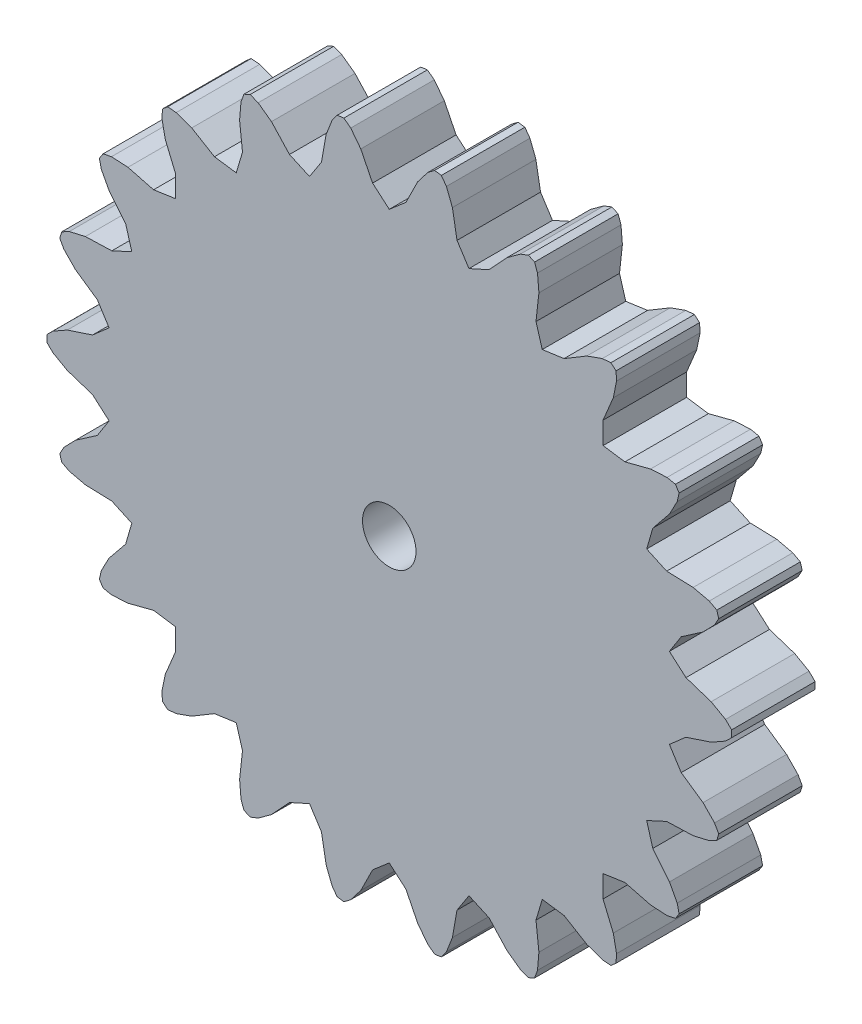
SolidWorks part; units mm, degrees
ref_plane "Front Plane" through (0, 0, 0) normal (0, 0, 1) x (1, 0, 0)
ref_plane "Top Plane" through (0, 0, 0) normal (0, 1, 0) x (1, 0, 0)
ref_plane "Right Plane" through (0, 0, 0) normal (1, 0, 0) x (0, 0, -1)
sketch "Sketch1" plane through (0, 0, 0) normal (0, 0, 1) x (1, 0, 0)
  line L1 (1.2374, -1.2374) -> (-1.2374, -1.2374) construction
  line L2 (1.2374, -1.2374) -> (1.2374, 1.2374) construction
  line L3 (1.2374, 1.2374) -> (-1.2374, 1.2374) construction
  line L4 (-1.2374, -1.2374) -> (-1.2374, 1.2374) construction
  line L5 (1.2374, -1.2374) -> (-1.2374, 1.2374) construction
  line L6 (1.2374, 1.2374) -> (-1.2374, -1.2374) construction
  circle A0 centre (0, 0) radius 20.5
  circle A1 centre (0, 0) radius 1.75 construction
  dimension "D1" = 41
  dimension "D2" = 3.5
extrude "Boss-Extrude1" add sketch "Sketch1" along normal blind 5
sketch "Sketch2" plane through (0, 0, 0) normal (0, 0, 1) x (1, 0, 0)
  line L0 (0, 0) -> (0, 10.088) construction
  line L1 (0, 16.9447) -> (-0.9985, 17.8041)
  line L8 (-2.7154, 20.3194) -> (0, 24.5037)
  line L11 (-0.9985, 17.8041) -> (-1.7043, 19.2252)
  line L12 (-1.7043, 19.2252) -> (-2.3066, 20.0063)
  line L13 (-2.3066, 20.0063) -> (-2.7154, 20.3194)
  line L14 (2.3066, 20.0063) -> (2.7154, 20.3194)
  line L15 (1.7043, 19.2252) -> (2.3066, 20.0063)
  line L16 (0.9985, 17.8041) -> (1.7043, 19.2252)
  line L17 (2.7154, 20.3194) -> (0, 24.5037)
  line L18 (0, 16.9447) -> (0.9985, 17.8041)
  circle A14 centre (0, 0) radius 20.5 construction
  point P16 (0, 20.5)
extrude "Cut-Extrude1" cut sketch "Sketch2" along normal through all
sketch "Sketch3" plane through (0, 0, 0) normal (0, 0, 1) x (1, 0, 0)
  circle A0 centre (0, 0) radius 7.5
  dimension "D1" = 15
sketch "Sketch4" plane through (0, 0, 5) normal (0, 0, 1) x (1, 0, 0)
  circle A0 centre (0, 0) radius 1.6
  dimension "D1" = 3.2
extrude "Cut-Extrude2" cut sketch "Sketch4" against normal through all both and the other way through all
pattern_circular "CirPattern1" count 22 over 360 about axis through (0, 0, 0) along (0, 0, 1) of "Cut-Extrude1"
equation "\"circle\"=41"
equation "\"D1@Sketch1\"=\"circle\""
equation "\"separator_width\"=45"
equation "\"big-gear-thiccness\"=2"
equation "\"D1@Boss-Extrude1\"=10/2"
